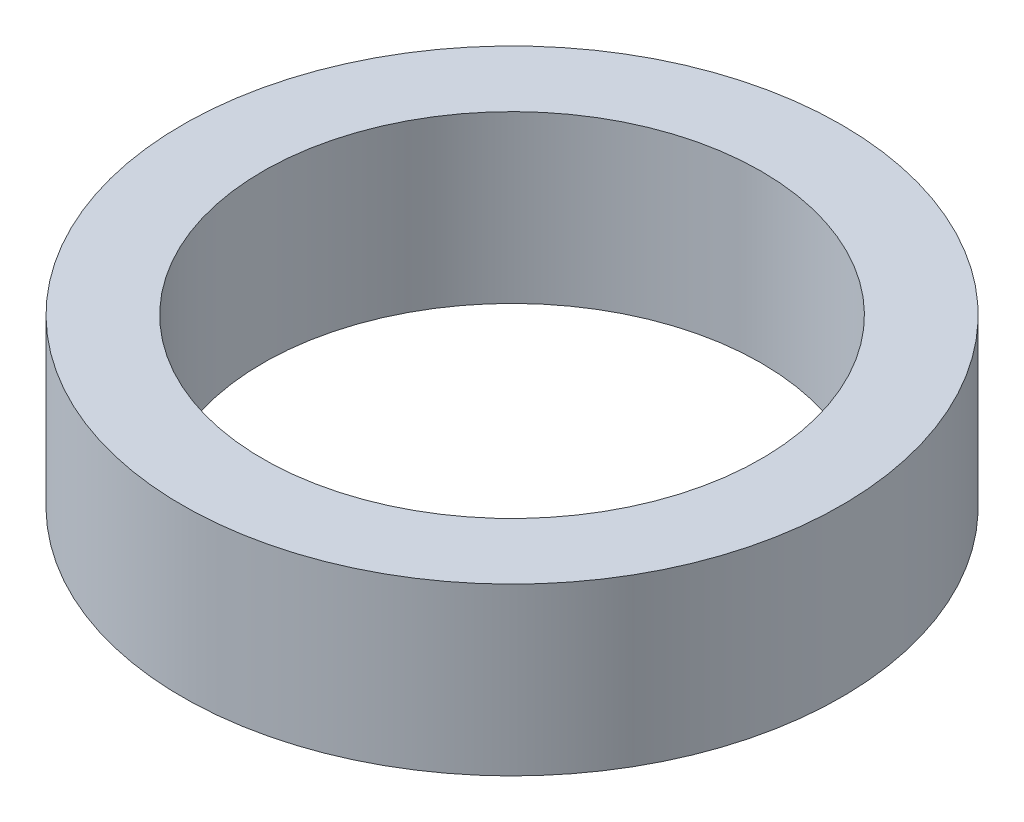
SolidWorks part; units mm, degrees
material "6061 Alloy"
ref_plane "Front Plane" through (0, 0, 0) normal (0, 0, 1) x (1, 0, 0)
ref_plane "Top Plane" through (0, 0, 0) normal (0, 1, 0) x (1, 0, 0)
ref_plane "Right Plane" through (0, 0, 0) normal (1, 0, 0) x (0, 0, -1)
sketch "Sketch1" plane through (0, 0, 0) normal (0, 0, 1) x (1, 0, 0)
  line L0 (0, 0) -> (0, 3.0292) construction
  line L1 (-2.3813, 1.5875) -> (-2.3813, 0)
  line L2 (-2.3813, 0) -> (-3.1496, 0)
  line L3 (-3.1496, 0) -> (-3.1496, 1.5875)
  line L4 (-3.1496, 1.5875) -> (-2.3813, 1.5875)
  dimension "D1" = 4.7625
  dimension "D2" = 6.2992
  dimension "D3" = 1.5875
revolve "Revolve1" add sketch "Sketch1" angle 360 about L0
